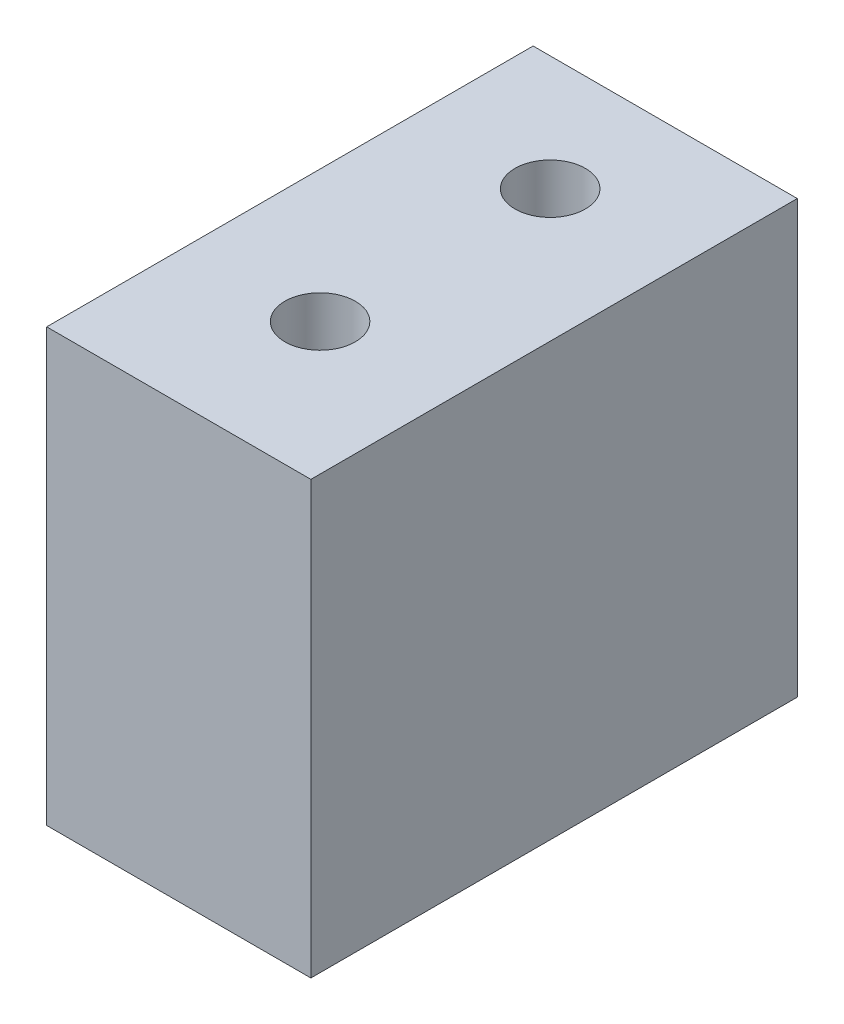
SolidWorks part; units mm, degrees
ref_plane "Plan de face" through (0, 0, 0) normal (0, 0, 1) x (1, 0, 0)
ref_plane "Plan de dessus" through (0, 0, 0) normal (0, 1, 0) x (1, 0, 0)
ref_plane "Plan de droite" through (0, 0, 0) normal (1, 0, 0) x (0, 0, -1)
sketch "Esquisse1" plane through (0, 0, 0) normal (0, 0, 1) x (1, 0, 0)
  line L1 (0, 0) -> (-15, 0)
  line L2 (0, 0) -> (0, 24.52)
  line L3 (0, 24.52) -> (-15, 24.52)
  line L4 (-15, 0) -> (-15, 24.52)
  dimension "D1" = 15
  dimension "D2" = 24.52
extrude "Boss.-Extru.1" add sketch "Esquisse1" against normal blind 27.62
sketch "Esquisse2" plane through (0, 24.52, 0) normal (0, 1, 0) x (1, 0, 0)
  line L0 (0, 1.49) -> (-15, 1.49)
  line L1 (0, 27.62) -> (0, 0) construction
  line L2 (-15, 27.62) -> (-15, 0) construction
  line L3 (0, 0) -> (-15, 0) construction
  line L4 (-7.5, 14.555) -> (-7.5, 27.62)
  line L6 (-7.5, 14.555) -> (-15, 14.555)
  line L7 (0, 27.62) -> (-15, 27.62) construction
  line L8 (-7.5, 14.555) -> (-7.5, 1.49)
  circle A0 centre (-7.5, 21.0875) radius 2
  circle A1 centre (-7.5, 8.0225) radius 2
  point P18 (-39.9254, 58.2673)
  dimension "D1" = 1.49
extrude "Enlèv. mat.-Extru.1" cut sketch "Esquisse2" against normal blind 3 contours L4 A0 | L4 A0 | L8 A1 | L8 A1
sketch "Esquisse3" plane through (0, 0, 0) normal (0, -1, 0) x (1, 0, 0)
  line L0 (0, -13.81) -> (-15, -13.81)
  line L1 (0, -27.62) -> (0, 0) construction
  line L2 (-15, -27.62) -> (-15, 0) construction
  line L3 (-7.5, -13.81) -> (-7.5, -27.62)
  line L4 (-15, -27.62) -> (0, -27.62) construction
  line L5 (-7.5, -13.81) -> (-7.5, 0)
  line L6 (-15, 0) -> (0, 0) construction
  circle A0 centre (-7.5, -20.715) radius 2
  circle A1 centre (-7.5, -6.905) radius 2
extrude "Enlèv. mat.-Extru.2" cut sketch "Esquisse3" against normal blind 3 contours L5 A1 | L5 A1 | L3 A0 | L3 A0
